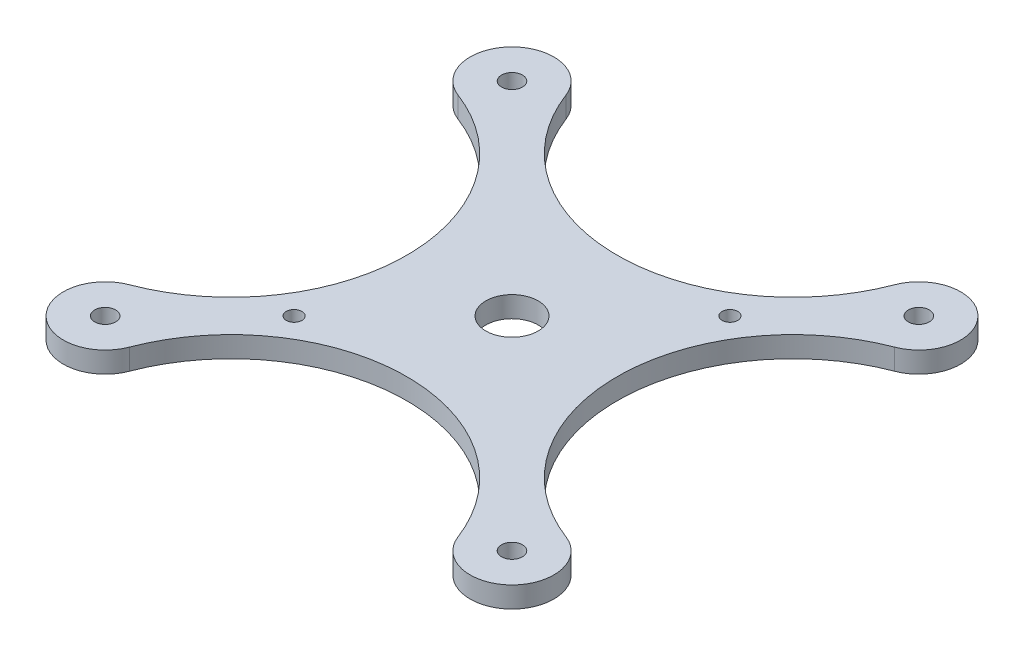
SolidWorks part; units mm, degrees
material "PET"
ref_plane "Front Plane" through (0, 0, 0) normal (0, 0, 1) x (1, 0, 0)
ref_plane "Top Plane" through (0, 0, 0) normal (0, 1, 0) x (1, 0, 0)
ref_plane "Right Plane" through (0, 0, 0) normal (1, 0, 0) x (0, 0, -1)
sketch "Sketch1" plane through (0, 0, 0) normal (0, 1, 0) x (1, 0, 0)
  line L17 (0, 20.1) -> (0, -20.1) construction
  line L22 (-38.8909, 38.8909) -> (38.8909, -38.8909) construction
  line L29 (0, -55) -> (0, 55) construction
  line L31 (38.8909, 38.8909) -> (-38.8909, -38.8909) construction
  line L36 (-55, 0) -> (55, 0) construction
  circle A8 centre (0, 0) radius 55 construction
  circle A9 centre (-38.8909, 38.8909) radius 2
  circle A10 centre (38.8909, 38.8909) radius 2
  circle A11 centre (38.8909, -38.8909) radius 2
  circle A12 centre (-38.8909, -38.8909) radius 2
  arc A13 (-31.4161, 41.7417) -> (31.4161, 41.7417) centre (0, 53.7233) ccw
  arc A14 (41.7417, 31.4161) -> (41.7417, -31.4161) centre (53.7233, 0) ccw
  arc A15 (31.4161, -41.7417) -> (-31.4161, -41.7417) centre (0, -53.7233) ccw
  arc A16 (-41.7417, -31.4161) -> (-41.7417, 31.4161) centre (-53.7233, 0) ccw
  arc A17 (-31.4161, 41.7417) -> (-41.7417, 31.4161) centre (-38.8909, 38.8909) ccw
  arc A18 (41.7417, 31.4161) -> (31.4161, 41.7417) centre (38.8909, 38.8909) ccw
  arc A19 (31.4161, -41.7417) -> (41.7417, -31.4161) centre (38.8909, -38.8909) ccw
  arc A20 (-41.7417, -31.4161) -> (-31.4161, -41.7417) centre (-38.8909, -38.8909) ccw
  circle A21 centre (0, 0) radius 5
  circle A22 centre (20.8314, 20.8314) radius 1.5
  circle A23 centre (-20.8314, -20.8314) radius 1.5
  point P6 (0, 0)
  dimension "D1" = 4
  dimension "D2" = 110
  dimension "D3" = 8
  dimension "D4" = 40.2
  dimension "D5" = 10
  dimension "D7" = 3
  dimension "D6" = 58.92
extrude "Boss-Extrude1" add sketch "Sketch1" along normal blind 4
